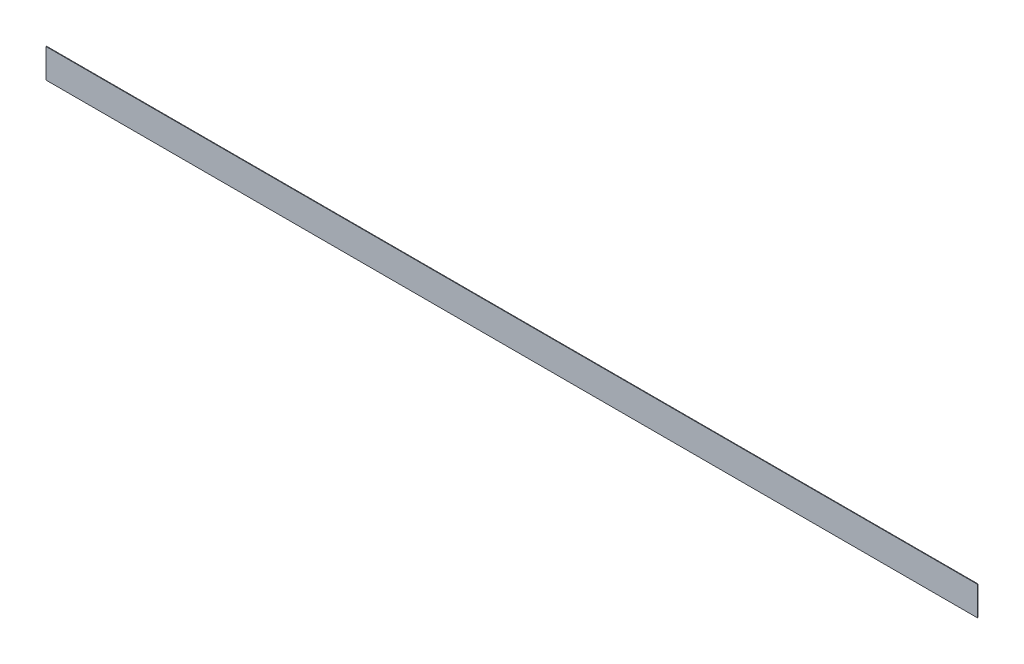
SolidWorks part; units mm, degrees
ref_plane "Front Plane" through (0, 0, 0) normal (0, 0, 1) x (1, 0, 0)
ref_plane "Top Plane" through (0, 0, 0) normal (0, 1, 0) x (1, 0, 0)
ref_plane "Right Plane" through (0, 0, 0) normal (1, 0, 0) x (0, 0, -1)
sketch "Sketch1" plane through (0, 0, 0) normal (0, 0, 1) x (1, 0, 0)
  line L1 (0, 0) -> (160, 0)
  line L2 (0, 0) -> (0, -5)
  line L3 (0, -5) -> (160, -5)
  line L4 (160, 0) -> (160, -5)
  dimension "D1" = 5
  dimension "D2" = 160
extrude "Boss-Extrude1" add sketch "Sketch1" along normal blind 0.1
